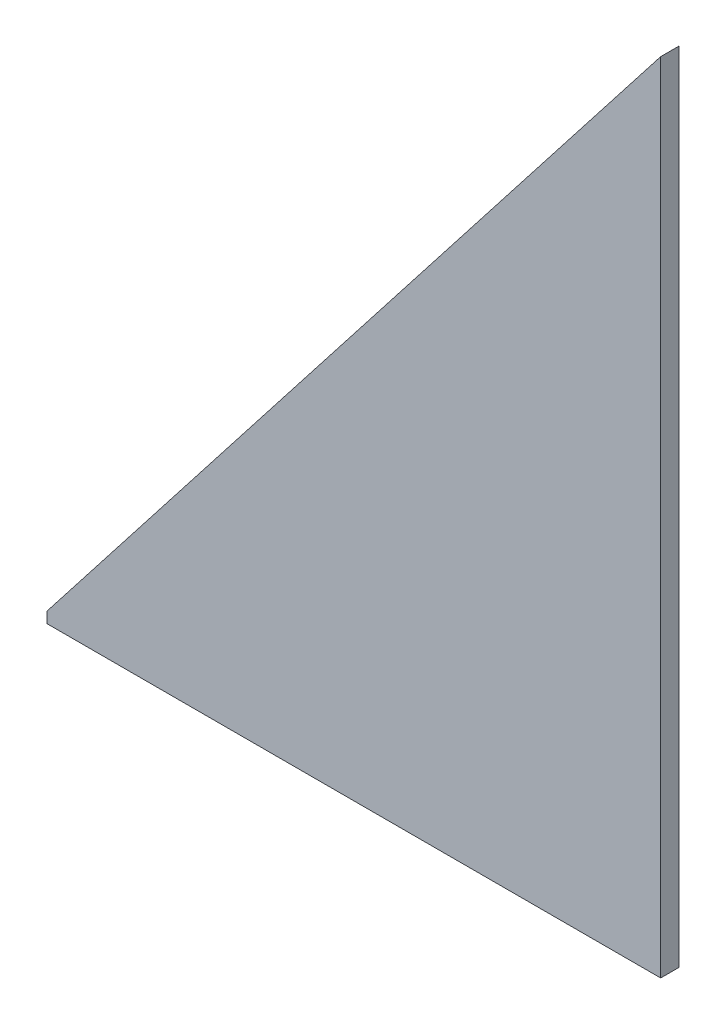
SolidWorks part; units mm, degrees
ref_plane "前视基准面" through (0, 0, 0) normal (0, 0, 1) x (1, 0, 0)
ref_plane "上视基准面" through (0, 0, 0) normal (0, 1, 0) x (1, 0, 0)
ref_plane "右视基准面" through (0, 0, 0) normal (1, 0, 0) x (0, 0, -1)
sketch "草图1" plane through (0, 0, 0) normal (0, 0, 1) x (1, 0, 0)
  line L1 (-77.8102, 30.4569) -> (22.1898, 30.4569)
  line L2 (-77.8102, 30.4569) -> (-77.8102, -99.5431)
  line L3 (-77.8102, -99.5431) -> (22.1898, -99.5431)
  line L4 (22.1898, 30.4569) -> (22.1898, -99.5431)
  dimension "D1" = 100
  dimension "D2" = 130
extrude "凸台-拉伸1" add sketch "草图1" along normal blind 3
sketch "草图2" plane through (0, 0, 0) normal (0, 0, 1) x (1, 0, 0)
  line L0 (-77.8102, 30.4569) -> (22.1898, 30.4569)
  line L1 (-77.8102, 30.4569) -> (-77.8102, -97.7897)
  line L2 (-77.8102, 30.4569) -> (-77.8102, -99.5431) construction
  line L3 (-77.8102, -97.7897) -> (22.1898, 30.4569)
extrude "切除-拉伸5" cut sketch "草图2" along normal through all
